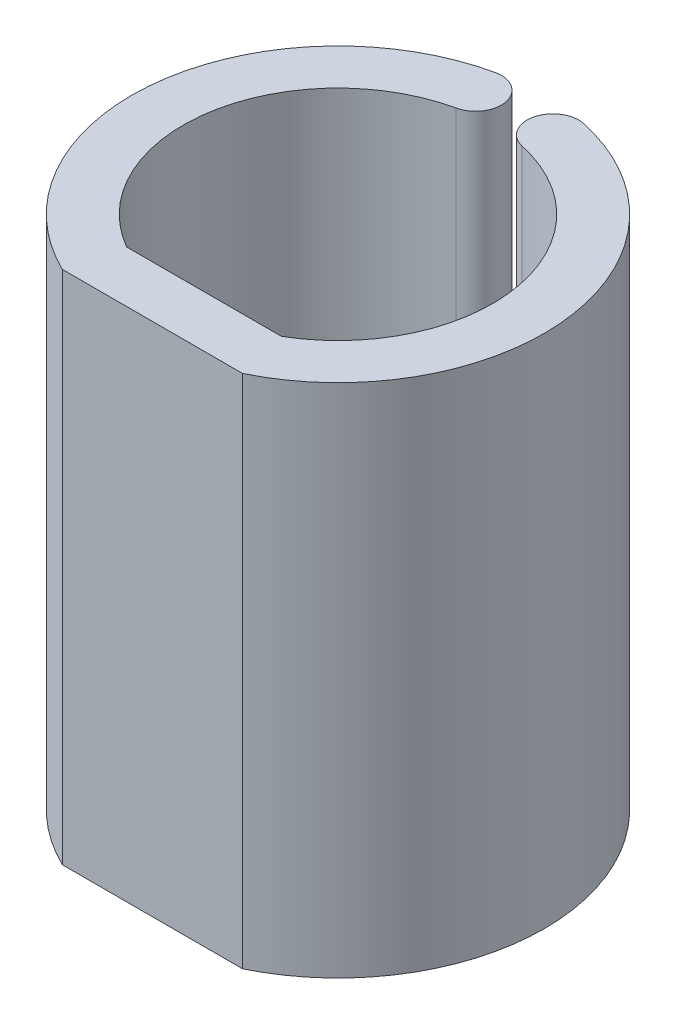
SolidWorks part; units mm, degrees
ref_plane "Front Plane" through (0, 0, 0) normal (0, 0, 1) x (1, 0, 0)
ref_plane "Top Plane" through (0, 0, 0) normal (0, 1, 0) x (1, 0, 0)
ref_plane "Right Plane" through (0, 0, 0) normal (1, 0, 0) x (0, 0, -1)
sketch "Sketch1" plane through (0, 0, 0) normal (0, 1, 0) x (1, 0, 0)
  line L4 (1.5, 0) -> (-1.5, 0)
  line L5 (-0.25, 6.8371) -> (-0.25, 5.3719) construction
  line L6 (0.25, 5.3719) -> (0.25, 6.7835) construction
  line L7 (1.7475, -1) -> (-1.7475, -1)
  arc A2 (-1.5, 0) -> (-0.6429, 5.5284) centre (0, 2.5981) cw
  arc A3 (1.5, 0) -> (0.6429, 5.5284) centre (0, 2.5981) ccw
  arc A4 (1.7475, -1) -> (0.8571, 6.5052) centre (0, 2.5981) ccw
  arc A6 (-1.7475, -1) -> (-0.8571, 6.5052) centre (0, 2.5981) cw
  arc A7 (0.6429, 5.5284) -> (0.8571, 6.5052) centre (0.75, 6.0168) cw
  arc A9 (-0.8571, 6.5052) -> (-0.6429, 5.5284) centre (-0.75, 6.0168) cw
  arc A10 (-0.6429, 5.5284) -> (-0.475, 5.5429) centre (-0.6035, 6.0507) ccw construction
  arc A11 (0.6429, 5.5284) -> (0.78, 6.5291) centre (1.0175, 5.9868) cw construction
  arc A12 (1.7475, -1) -> (1.1503, 6.4291) centre (0, 2.5981) ccw construction
  arc A13 (-1.7475, -1) -> (-0.8571, 6.5052) centre (0, 2.5981) cw construction
  arc A14 (-0.8571, 6.5052) -> (-0.8571, 6.5052) centre (-0.8571, 6.5052) ccw construction
  arc A15 (1.1503, 6.4291) -> (1.1503, 6.4291) centre (1.1503, 6.4291) cw construction
  point P4 (0, 0)
  dimension "D1" = 3
  dimension "D2" = 3
  dimension "D5" = 1
  dimension "D3" = 3
  dimension "D4" = 0.5
extrude "Boss-Extrude1" add sketch "Sketch1" along normal mid plane 10
